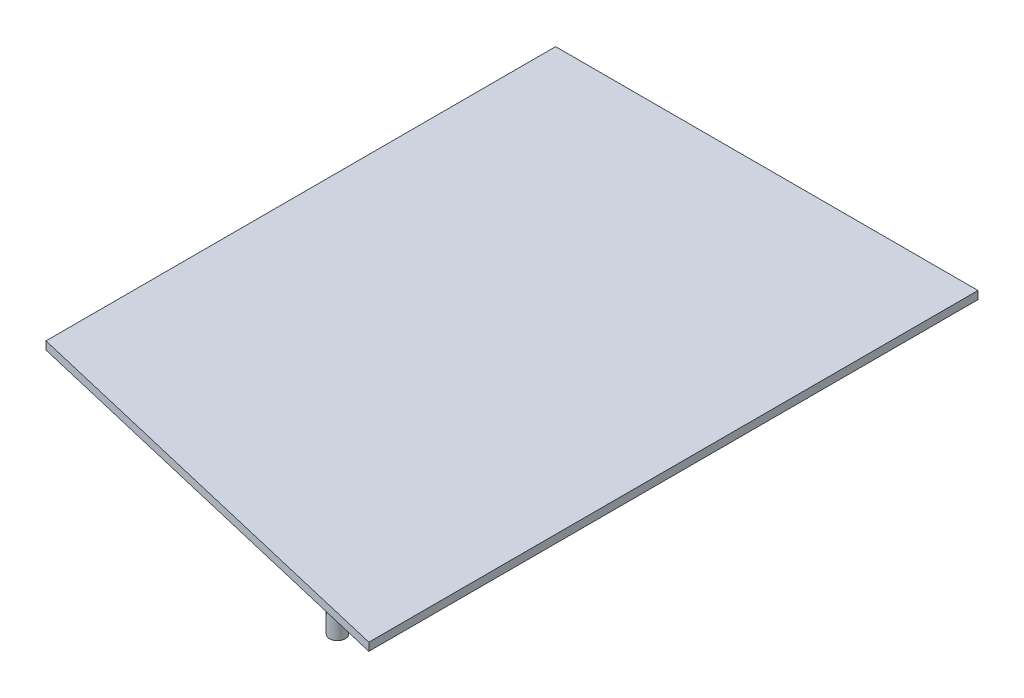
SolidWorks part; units mm, degrees
ref_plane "Front Plane" through (0, 0, 0) normal (0, 0, 1) x (1, 0, 0)
ref_plane "Top Plane" through (0, 0, 0) normal (0, 1, 0) x (1, 0, 0)
ref_plane "Right Plane" through (0, 0, 0) normal (1, 0, 0) x (0, 0, -1)
sketch "Sketch1" plane through (0, 0, 0) normal (0, 1, 0) x (1, 0, 0)
  line L0 (0, 0) -> (0, 80)
  line L1 (0, 80) -> (66.3, 80)
  line L2 (66.3, 80) -> (66.3, -15.6238)
  line L3 (66.3, -15.6238) -> (0, 0)
  dimension "D1" = 66.3
  dimension "D2" = 103.26
  dimension "D3" = 80
extrude "Boss-Extrude1" add sketch "Sketch1" along normal blind 1.25
sketch "Sketch2" plane through (0, 0, 0) normal (0, -1, 0) x (1, 0, 0)
  line L0 (0, -80) -> (0, 0) construction
  line L1 (0, 0) -> (66.3, 15.6238) construction
  line L2 (66.3, -80) -> (0, -80) construction
  line L3 (57.75, -78.75) -> (55.25, -78.75)
  line L4 (57.75, -78.75) -> (57.75, -76.25)
  line L5 (57.75, -76.25) -> (55.25, -76.25)
  line L6 (55.25, -78.75) -> (55.25, -76.25)
  line L7 (3.75, -26.25) -> (1.25, -26.25)
  line L8 (3.75, -26.25) -> (3.75, -23.75)
  line L9 (3.75, -23.75) -> (1.25, -23.75)
  line L10 (1.25, -26.25) -> (1.25, -23.75)
  circle A0 centre (56.5, 10.7459) radius 1.25
  point P14 (55.25, -77.5)
  dimension "D1" = 56.5
  dimension "D2" = 2.5
  dimension "D3" = 2.5
  dimension "D4" = 55.25
  dimension "D5" = 2.5
  dimension "D6" = 2.5
  dimension "D7" = 1.25
  dimension "D8" = 2.5
  dimension "D9" = 2.5
  dimension "D10" = 1.25
  dimension "D11" = 53.75
extrude "Boss-Extrude2" add sketch "Sketch2" along normal blind 5
sketch "Sketch3" plane through (0, 0, 0) normal (0, -1, 0) x (-1, 0, 0)
  line L0 (-61.3, 75) -> (-61.3, -9.3086)
  line L1 (-61.3, -9.3086) -> (-5, 3.9587)
  line L2 (-5, 3.9587) -> (-5, 75)
  line L3 (-5, 75) -> (-61.3, 75)
  line L5 (-66.3, -15.6238) -> (-66.3, 80) construction
  line L6 (0, 80) -> (0, 0) construction
  line L8 (0, 0) -> (-66.3, -15.6238) construction
  line L9 (-66.3, 80) -> (0, 80) construction
  dimension "D1" = 5
  dimension "D2" = 5
  dimension "D3" = 5
  dimension "D4" = 5
  dimension "D5" = 5
  dimension "D6" = 5
extrude "Cut-Extrude1" cut sketch "Sketch3" against normal blind 0.6
